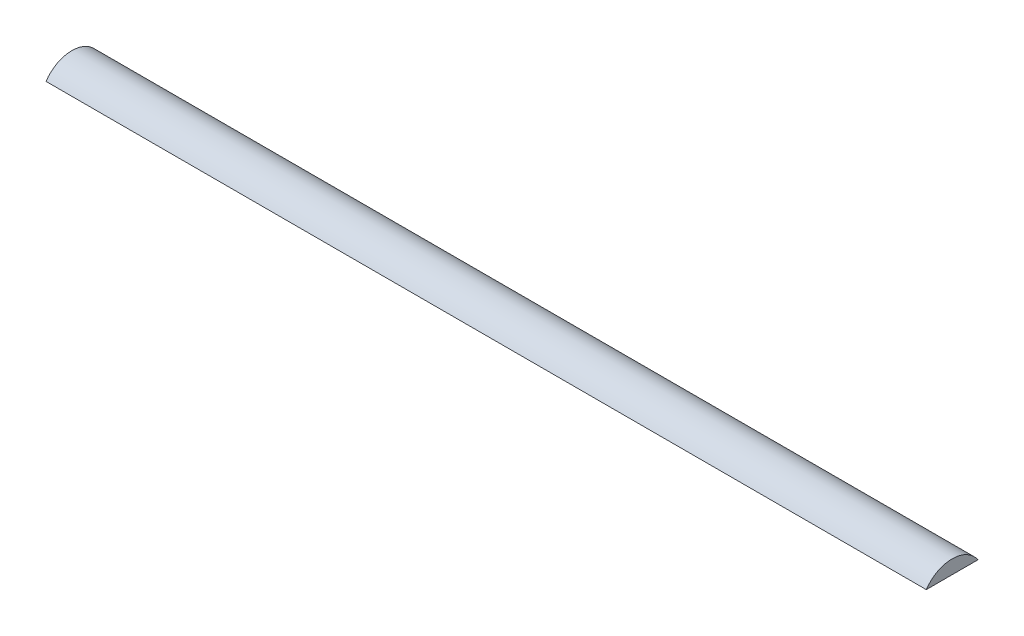
SolidWorks part; units mm, degrees
ref_plane "前视基准面" through (0, 0, 0) normal (0, 0, 1) x (1, 0, 0)
ref_plane "上视基准面" through (0, 0, 0) normal (0, 1, 0) x (1, 0, 0)
ref_plane "右视基准面" through (0, 0, 0) normal (1, 0, 0) x (0, 0, -1)
sketch "草图1" plane through (0, 0, 0) normal (1, 0, 0) x (0, 0, -1)
  line L0 (23.5, 0) -> (-23.5, 0)
  line L1 (0, 0) -> (0, 12.5) construction
  arc A0 (23.5, 0) -> (-23.5, 0) centre (0, -15.84) ccw
  point P4 (0, 0)
  dimension "D1" = 47
  dimension "D2" = 12.5
extrude "凸台-拉伸1" add sketch "草图1" along normal blind 800
sketch "草图2" plane through (0, 0, 0) normal (0, -1, 0) x (1, 0, 0)
  line L0 (0, 0) -> (-50000, 0) construction
